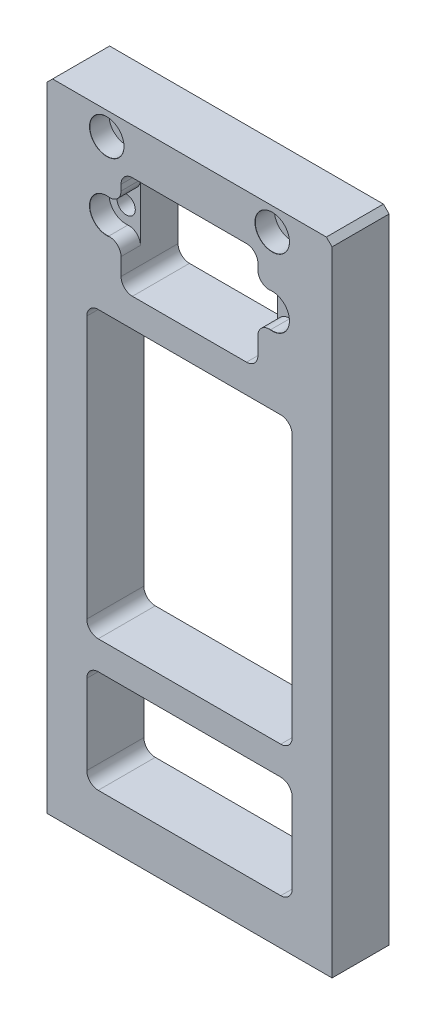
SolidWorks part; units mm, degrees
material "6061 Alloy"
ref_plane "Front Plane" through (0, 0, 0) normal (0, 0, 1) x (1, 0, 0)
ref_plane "Top Plane" through (0, 0, 0) normal (0, 1, 0) x (1, 0, 0)
ref_plane "Right Plane" through (0, 0, 0) normal (1, 0, 0) x (0, 0, -1)
sketch "Sketch1" plane through (0, 0, 0) normal (0, 0, 1) x (1, 0, 0)
  line L2 (25, -112) -> (-25, -112)
  line L3 (25, -112) -> (25, 0)
  line L4 (25, 0) -> (-25, 0)
  line L5 (-25, -112) -> (-25, 0)
  line L8 (0, 0) -> (0, -112) construction
  line L9 (-12, -8) -> (12, -8)
  line L10 (-12, -8) -> (-12, -26)
  line L11 (-12, -26) -> (12, -26)
  line L12 (12, -8) -> (12, -26)
  point P13 (-14.5, -4)
  point P15 (14.5, -4)
  point P16 (-14.5, -16)
  point P18 (14.5, -16)
  dimension "D1" = 50
  dimension "D2" = 112
  dimension "D3" = 18
  dimension "D4" = 24
  dimension "D5" = 8
  dimension "D6" = 12
  dimension "D7" = 4
  dimension "D8" = 29
extrude "Boss-Extrude1" add sketch "Sketch1" along normal blind 10
sketch "Sketch8" plane through (0, 0, 10) normal (0, 0, 1) x (1, 0, 0)
  line L0 (0, 0) -> (0, -112) construction
  line L1 (-18, -31) -> (18, -31)
  line L2 (-18, -31) -> (-18, -81)
  line L3 (-18, -81) -> (18, -81)
  line L4 (18, -31) -> (18, -81)
  line L5 (-18, -86) -> (18, -86)
  line L6 (-18, -86) -> (-18, -104)
  line L7 (-18, -104) -> (18, -104)
  line L8 (18, -86) -> (18, -104)
  line L10 (-12, -26) -> (12, -26) construction
  line L11 (-25, -112) -> (25, -112) construction
  line L12 (-12, -8) -> (-12, -26) construction
  line L13 (25, 0) -> (-25, 0) construction
  line L14 (-25, 0) -> (-25, -112) construction
  dimension "D1" = 5
  dimension "D2" = 5
  dimension "D3" = 8
  dimension "D4" = 7
extrude "Cut-Extrude1" cut sketch "Sketch8" against normal through all
sketch "Sketch2" plane through (0, 0, 10) normal (0, 0, 1) x (1, 0, 0)
  point P0 (-14.5, -4)
  point P1 (-14.5, -16)
  point P3 (14.5, -4)
  point P5 (14.5, -16)
hole_wizard "CBORE for M3 Hexagon socket head cap screws3" positions "Sketch6" profile "Sketch7" counterbore size "M3" standard "GB" end condition through all
sketch "Sketch6" plane through (0, 0, 10) normal (0, 0, 1) x (1, 0, 0)
  point P0 (-14.5, -4)
  point P3 (-14.5, -16)
  point P6 (14.5, -4)
  point P9 (14.5, -16)
sketch "Sketch7" plane through (-14.5, -4, 10) normal (1, 0, 0) x (0, -1, 0)
  line L0 (0, 0) -> (0, 10)
  line L1 (0, 10) -> (1.6, 10)
  line L3 (1.6, 10) -> (1.6, 3.4)
  line L4 (3, 3.4) -> (1.6, 3.4)
  line L5 (3, 3.4) -> (3, 0.025)
  line L6 (3, 0.025) -> (3.025, 0)
  line L7 (3.025, 0) -> (0, 0)
  line L8 (-3, 0.025) -> (-3.025, 0) construction
  line L11 (0, -6.35) -> (0, 107.95) construction
  dimension "Thru Hole Dia." = 3.2
  dimension "Thru Hole Depth" = 10
  dimension "C'Bore Dia." = 6
  dimension "C'Bore Depth" = 3.4
  dimension "Near C'Sink Dia." = 6.05
  dimension "Near C'Sink Angle" = 90
chamfer "Chamfer1" distance 1 angle 45 2 edges at (-25, 0, 5) (25, 0, 5)
fillet "Fillet1" radius 2 16 edges at (-12, -8, 5) (-12, -26, 5) (12, -26, 5) (12, -8, 5) (-12, -14.3417, 8.2875) (-12, -17.6583, 8.2875) (12, -17.6583, 8.2875) (12, -14.3417, 8.2875) (18, -86, 5) (18, -104, 5) (-18, -104, 5) (-18, -86, 5) (18, -31, 5) (18, -81, 5) (-18, -81, 5) (-18, -31, 5)
sketch "Sketch9" plane through (0, -112, 0) normal (0, -1, 0) x (1, 0, 0)
  line L0 (-25, 5) -> (25, 5) construction
  line L1 (-25, 10) -> (-25, 0) construction
  line L2 (25, 10) -> (25, 0) construction
  line L3 (0, -55) -> (0, 55) construction
  point P0 (-21.75, 5)
  point P10 (21.75, 5)
  dimension "D1" = 3.25
hole_wizard "M3 Tapped Hole1" positions "3DSketch2" profile "Sketch10" tap size "M3" standard "GB"
sketch3d "3DSketch2"
  point P0 (-21.75, -112, 5)
  point P3 (21.75, -112, 5)
sketch "Sketch10" plane through (-21.75, -112, 5) normal (1, 0, 0) x (0, 0, -1)
  line L0 (0, 0) -> (0, 10.2511)
  line L1 (0, 10.2511) -> (1.25, 9.5)
  line L2 (1.25, 9.5) -> (1.25, 0.275)
  line L3 (1.25, 0.275) -> (1.525, 0)
  line L5 (1.525, 0) -> (0, 0)
  line L6 (-1.25, 0.275) -> (-1.525, 0) construction
  line L10 (0, 10.2511) -> (-1.25, 9.5) construction
  line L11 (0, -6.35) -> (0, 107.95) construction
  dimension "Tap Drill Dia." = 2.5
  dimension "Tap Drill Depth" = 9.5
  dimension "Near C'Sink Dia." = 3.05
  dimension "Near C'Sink Angle" = 90
  dimension "Drill Angle" = 118
